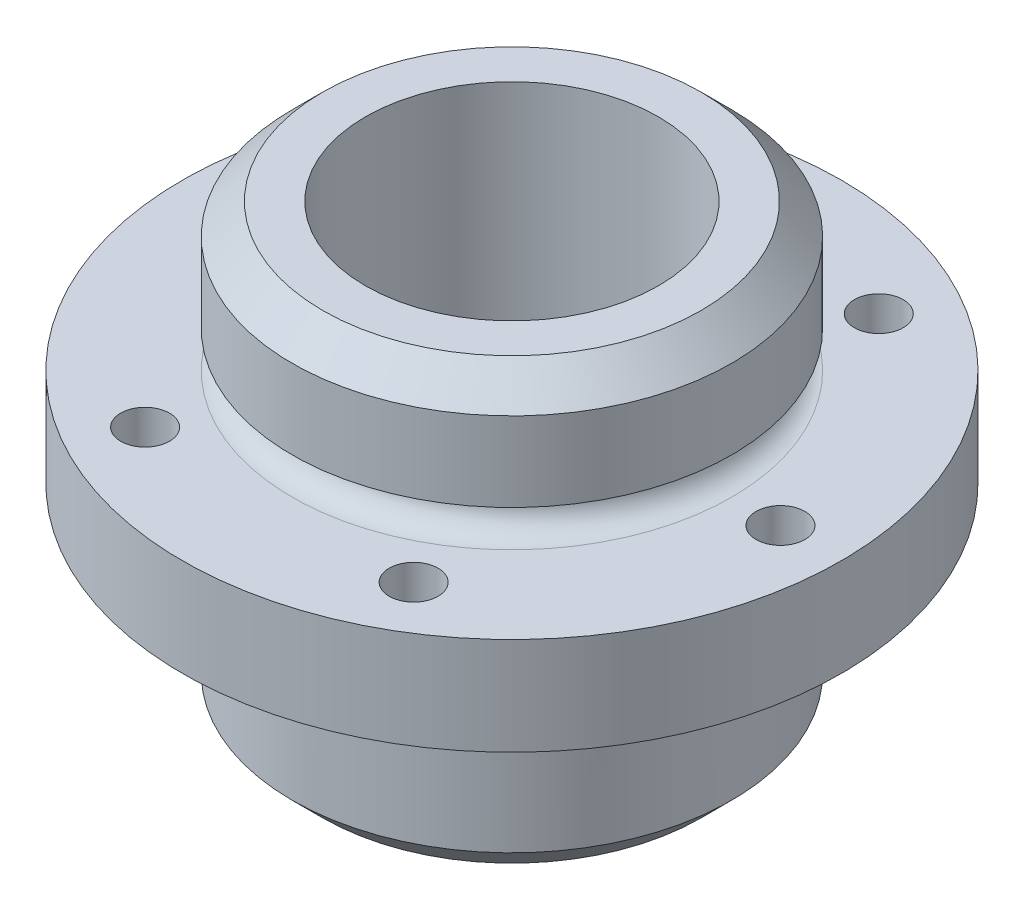
SolidWorks part; units mm, degrees
ref_plane "Front Plane" through (0, 0, 0) normal (0, 0, 1) x (1, 0, 0)
ref_plane "Top Plane" through (0, 0, 0) normal (0, 1, 0) x (1, 0, 0)
ref_plane "Right Plane" through (0, 0, 0) normal (1, 0, 0) x (0, 0, -1)
sketch "Sketch1" plane through (0, 0, 0) normal (0, 0, 1) x (1, 0, 0)
  line L0 (0, 0) -> (0, 38688.1073) construction
  line L1 (-24, 35.6647) -> (-36, 35.6647)
  line L2 (-36, 35.6647) -> (-36, 17.6647)
  line L3 (-36, 17.6647) -> (-32, 17.6647)
  line L4 (-32, 17.6647) -> (-32, 11.6647)
  line L5 (-32, 11.6647) -> (-54, 11.6647)
  line L6 (-54, 11.6647) -> (-54, -4.3353)
  line L7 (-54, -4.3353) -> (-32, -4.3353)
  line L8 (-32, -4.3353) -> (-32, -6.1758)
  line L9 (-34.6601, -12.3353) -> (-36, -12.3353)
  line L10 (-36, -12.3353) -> (-36, -36.3353)
  line L11 (-36, -36.3353) -> (-24, -36.3353)
  line L12 (-24, -36.3353) -> (-24, 35.6647)
  arc A0 (-36, -12.3353) -> (-32, -6.1758) centre (-35.3301, -8.3918) ccw
  point P5 (-36, -24.3353)
  point P12 (0, 0)
  point P16 (-34, 17.6647)
  point P19 (-54, 3.6647)
  dimension "D12" = 4
  dimension "D1" = 24
  dimension "D2" = 36
  dimension "D3" = 32
  dimension "D4" = 54
  dimension "D5" = 32
  dimension "D6" = 36
  dimension "D7" = 32
  dimension "D8" = 8
  dimension "D9" = 16
  dimension "D10" = 24
  dimension "D11" = 6
revolve "Revolve1" add sketch "Sketch1" angle 360 about L0
chamfer "Chamfer2" distance 5 angle 45 2 edges at (0, -36.3353, -36) (0, 35.6647, -36)
fillet "Fillet1" radius 4 1 edges at (0, 11.6647, -32)
sketch "Sketch2" plane through (0, 11.6647, 0) normal (0, 1, 0) x (1, 0, 0)
  circle A0 centre (0, 0) radius 44 construction
  circle A1 centre (44, 0) radius 4
  circle A2 centre (22, -38.1051) radius 4
  circle A3 centre (-22, -38.1051) radius 4
  circle A4 centre (-44, 0) radius 4
  circle A5 centre (-22, 38.1051) radius 4
  circle A6 centre (22, 38.1051) radius 4
  point P17 (0, 0)
  dimension "D1" = 6
  dimension "D2" = 60
extrude "Cut-Extrude1" cut sketch "Sketch2" against normal up to next
